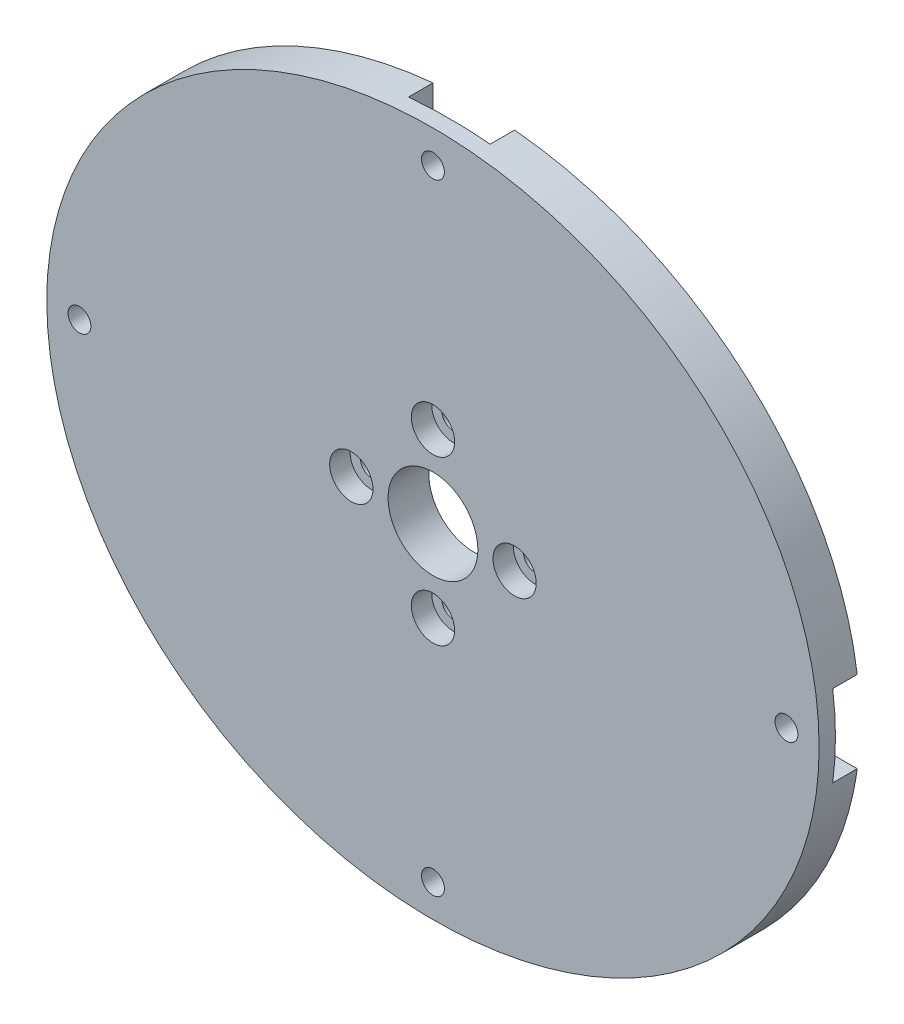
SolidWorks part; units mm, degrees
material "eSUN Tough Resin"
ref_plane "Front Plane" through (0, 0, 0) normal (0, 0, 1) x (1, 0, 0)
ref_plane "Top Plane" through (0, 0, 0) normal (0, 1, 0) x (1, 0, 0)
ref_plane "Right Plane" through (0, 0, 0) normal (1, 0, 0) x (0, 0, -1)
sketch "Sketch1" plane through (0, 0, 0) normal (0, 0, 1) x (1, 0, 0)
  line L0 (-1000, 0) -> (49000, 0) construction
  line L5 (0, -1000) -> (0, 49000) construction
  line L7 (-39.3, 34) -> (39.3, 34) construction
  line L8 (-39.3, 34) -> (-39.3, -34) construction
  line L9 (-39.3, -34) -> (39.3, -34) construction
  line L10 (39.3, 34) -> (39.3, -34) construction
  line L11 (-39.3, 34) -> (39.3, -34) construction
  line L12 (-39.3, -34) -> (39.3, 34) construction
  circle A0 centre (0, 0) radius 5.5
  circle A1 centre (-10, 0) radius 1.4
  circle A2 centre (0, 10) radius 1.4
  circle A3 centre (10, 0) radius 1.4
  circle A4 centre (0, -10) radius 1.4
  circle A6 centre (0, 38) radius 1.4
  circle A7 centre (-43.3, 0) radius 1.4
  circle A8 centre (43.3, 0) radius 1.4
  circle A9 centre (0, -38) radius 1.4
  ellipse E0 centre (0, 0) end of major axis (-47.3, 0) minor radius 42
  point P0 (0, 0)
  point P13 (0, 0)
  point P16 (0, 0)
  point P19 (0, 0)
  point P22 (0, 0)
  dimension "D1" = 11
  dimension "D2" = 2.8
  dimension "D5" = 8
  dimension "D7" = 2.8
  dimension "D8" = 68
  dimension "D3" = 10
  dimension "D6" = 8
  dimension "D9" = 4
  dimension "D10" = 4
  dimension "D11" = 78.6
  dimension "D4" = 4
extrude "Boss-Extrude1" add sketch "Sketch1" along normal blind 5
sketch "Sketch5" plane through (0, 0, 5) normal (0, 0, 1) x (1, 0, 0)
  circle A0 centre (10, 0) radius 1.4 construction
  circle A1 centre (0, -10) radius 1.4 construction
  circle A2 centre (-10, 0) radius 1.4 construction
  circle A3 centre (0, 10) radius 1.4 construction
  circle A4 centre (10, 0) radius 1.4
  circle A5 centre (0, -10) radius 1.4
  circle A6 centre (-10, 0) radius 1.4
  circle A7 centre (0, 10) radius 1.4
  circle A8 centre (0, 10) radius 2.65
  circle A9 centre (10, 0) radius 2.65
  circle A10 centre (0, -10) radius 2.65
  circle A11 centre (-10, 0) radius 2.65
  dimension "D1" = 1.25
  dimension "D2" = 1.25
  dimension "D3" = 1.25
  dimension "D4" = 1.25
extrude "Cut-Extrude3" cut sketch "Sketch5" against normal blind 2.5
sketch "Sketch6" plane through (0, 0, 0) normal (0, 0, -1) x (-1, 0, 0)
  line L0 (-5, 41.7647) -> (-5, 31.7647)
  line L1 (-5, 31.7647) -> (5, 31.7647)
  line L2 (5, 31.7647) -> (5, 41.7647)
  line L3 (-1000, 0) -> (66.7719, 0) construction
  line L4 (0, -1000) -> (0, 49000) construction
  line L5 (-46.9636, 5) -> (-36.9636, 5)
  line L6 (-36.9636, 5) -> (-36.9636, -5)
  line L7 (-36.9636, -5) -> (-46.9636, -5)
  line L8 (46.9636, 5) -> (36.9636, 5)
  line L9 (36.9636, 5) -> (36.9636, -5)
  line L10 (36.9636, -5) -> (46.9636, -5)
  line L11 (5, -31.7647) -> (5, -41.7647)
  line L12 (-5, -31.7647) -> (5, -31.7647)
  line L13 (-5, -41.7647) -> (-5, -31.7647)
  ellipse E0 centre (0, 0) end of major axis (47.3, 0) minor radius 42 construction
  ellipse E1 centre (0, 0) end of major axis (47.3, 0) minor radius 42 (-46.9636, 5) -> (-46.9636, -5) ccw
  ellipse E2 centre (0, 0) end of major axis (47.3, 0) minor radius 42 (5, 41.7647) -> (-5, 41.7647) ccw
  ellipse E3 centre (0, 0) end of major axis (-47.3, 0) minor radius 42 (46.9636, 5) -> (46.9636, -5) cw
  ellipse E4 centre (0, 0) end of major axis (47.3, 0) minor radius 42 (5, -41.7647) -> (-5, -41.7647) cw
  point P14 (0, 31.7647)
  dimension "D1" = 10
  dimension "D2" = 10
extrude "Cut-Extrude4" cut sketch "Sketch6" against normal blind 3
